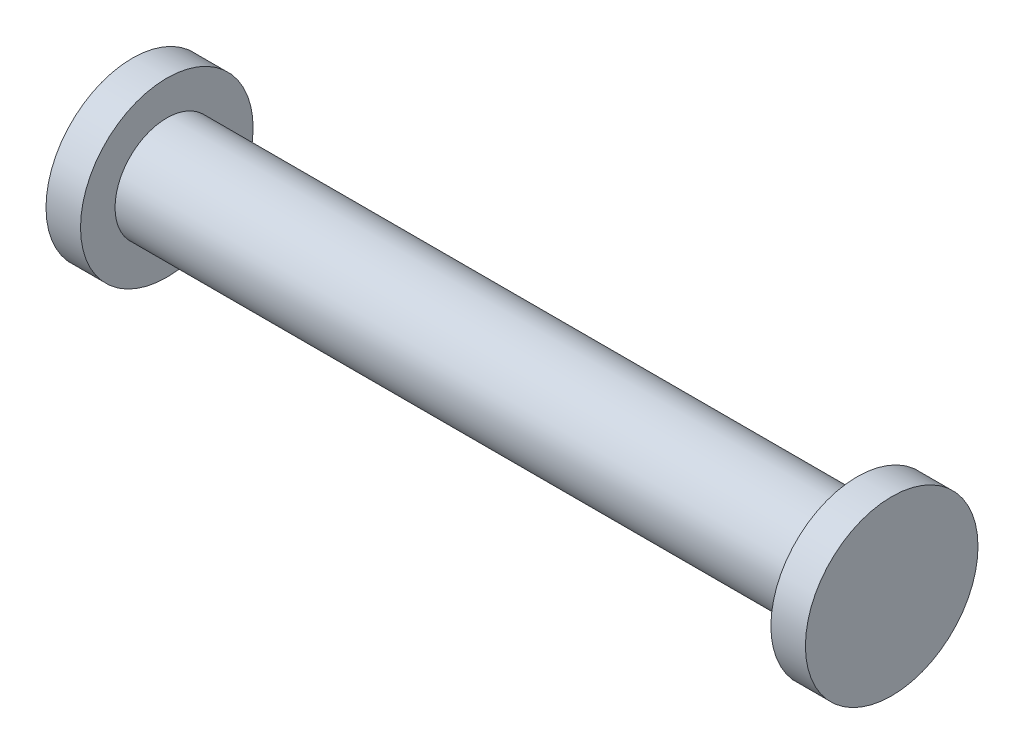
SolidWorks part; units mm, degrees
ref_plane "Front Plane" through (0, 0, 0) normal (0, 0, 1) x (1, 0, 0)
ref_plane "Top Plane" through (0, 0, 0) normal (0, 1, 0) x (1, 0, 0)
ref_plane "Right Plane" through (0, 0, 0) normal (1, 0, 0) x (0, 0, -1)
sketch "Sketch3" plane through (0, 0, 0) normal (0, 0, 1) x (1, 0, 0)
  line L1 (0, 0) -> (69.85, 0)
  line L2 (0, 0) -> (0, 4.7625)
  line L3 (0, 4.7625) -> (69.85, 4.7625)
  line L4 (69.85, 0) -> (69.85, 4.7625)
  line L5 (0, 4.7625) -> (3.175, 4.7625)
  line L6 (0, 4.7625) -> (0, 7.9375)
  line L7 (0, 7.9375) -> (3.175, 7.9375)
  line L8 (3.175, 4.7625) -> (3.175, 7.9375)
  line L9 (69.85, 4.7625) -> (66.675, 4.7625)
  line L10 (69.85, 4.7625) -> (69.85, 7.9375)
  line L11 (69.85, 7.9375) -> (66.675, 7.9375)
  line L12 (66.675, 4.7625) -> (66.675, 7.9375)
  dimension "D1" = 4.7625
  dimension "D2" = 69.85
  dimension "D3" = 3.175
  dimension "D4" = 3.175
revolve "Revolve1" add sketch "Sketch3" angle 360 about L1
